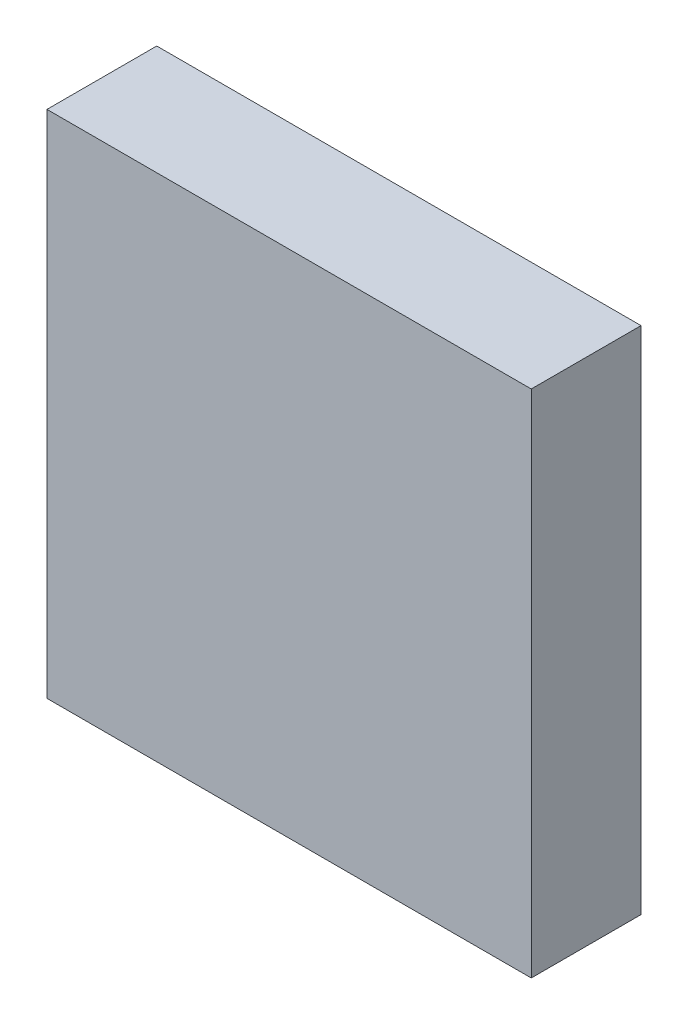
SolidWorks part; units mm, degrees
ref_plane "Front Plane" through (0, 0, 0) normal (0, 0, 1) x (1, 0, 0)
ref_plane "Top Plane" through (0, 0, 0) normal (0, 1, 0) x (1, 0, 0)
ref_plane "Right Plane" through (0, 0, 0) normal (1, 0, 0) x (0, 0, -1)
sketch "Sketch1" plane through (0, 0, 0) normal (0, 0, 1) x (1, 0, 0)
  line L1 (-37.5, 39.5) -> (37.5, 39.5)
  line L2 (-37.5, 39.5) -> (-37.5, -39.5)
  line L3 (-37.5, -39.5) -> (37.5, -39.5)
  line L4 (37.5, 39.5) -> (37.5, -39.5)
  line L5 (-37.5, 39.5) -> (37.5, -39.5) construction
  line L6 (-37.5, -39.5) -> (37.5, 39.5) construction
  point P0 (0, 0)
  dimension "D1" = 75
  dimension "D2" = 79
extrude "Boss-Extrude1" add sketch "Sketch1" along normal blind 17
